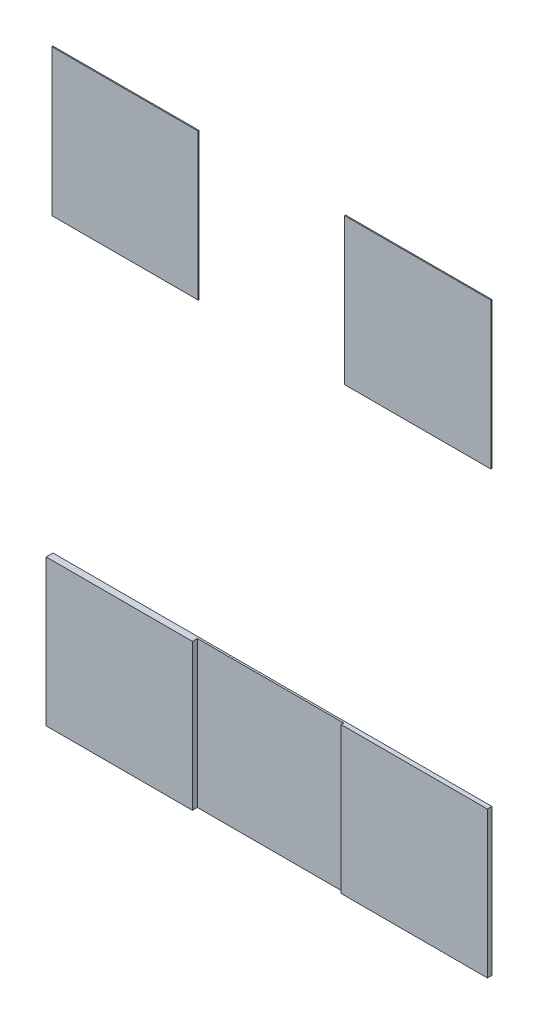
SolidWorks part; units mm, degrees
ref_plane "前视基准面" through (0, 0, 0) normal (0, 0, 1) x (1, 0, 0)
ref_plane "上视基准面" through (0, 0, 0) normal (0, 1, 0) x (1, 0, 0)
ref_plane "右视基准面" through (0, 0, 0) normal (1, 0, 0) x (0, 0, -1)
sketch "草图1" plane through (0, 0, 0) normal (0, 0, 1) x (1, 0, 0)
  line L1 (460, 460) -> (920, 460)
  line L2 (460, 460) -> (460, 920)
  line L3 (460, 920) -> (920, 920)
  line L4 (920, 460) -> (920, 920)
extrude "凸台-拉伸1" add sketch "草图1" along normal blind 21.42 flip side to cut
sketch "草图2" plane through (0, 0, 0) normal (0, 0, 1) x (1, 0, 0)
  line L1 (920, 460) -> (1380, 460)
  line L2 (920, 460) -> (920, 920)
  line L3 (920, 920) -> (1380, 920)
  line L4 (1380, 460) -> (1380, 920)
extrude "凸台-拉伸2" add sketch "草图2" along normal blind 5.8471 flip side to cut
sketch "草图3" plane through (0, 0, 0) normal (0, 0, 1) x (1, 0, 0)
  line L1 (1380, 460) -> (1840, 460)
  line L2 (1380, 460) -> (1380, 920)
  line L3 (1380, 920) -> (1840, 920)
  line L4 (1840, 460) -> (1840, 920)
extrude "凸台-拉伸3" add sketch "草图3" along normal blind 14.1569 flip side to cut
sketch "草图4" plane through (0, 0, 0) normal (0, 0, 1) x (1, 0, 0)
  line L1 (1840, 460) -> (2300, 460)
  line L2 (1840, 460) -> (1840, 920)
  line L3 (1840, 920) -> (2300, 920)
  line L4 (2300, 460) -> (2300, 920)
sketch "草图5" plane through (0, 0, 0) normal (0, 0, 1) x (1, 0, 0)
  line L1 (460, 920) -> (920, 920)
  line L2 (460, 920) -> (460, 1380)
  line L3 (460, 1380) -> (920, 1380)
  line L4 (920, 920) -> (920, 1380)
sketch "草图6" plane through (0, 0, 0) normal (0, 0, 1) x (1, 0, 0)
  line L1 (920, 920) -> (1380, 920)
  line L2 (920, 920) -> (920, 1380)
  line L3 (920, 1380) -> (1380, 1380)
  line L4 (1380, 920) -> (1380, 1380)
sketch "草图7" plane through (0, 0, 0) normal (0, 0, 1) x (1, 0, 0)
  line L1 (1380, 920) -> (1840, 920)
  line L2 (1380, 920) -> (1380, 1380)
  line L3 (1380, 1380) -> (1840, 1380)
  line L4 (1840, 920) -> (1840, 1380)
sketch "草图8" plane through (0, 0, 0) normal (0, 0, 1) x (1, 0, 0)
  line L1 (1840, 920) -> (2300, 920)
  line L2 (1840, 920) -> (1840, 1380)
  line L3 (1840, 1380) -> (2300, 1380)
  line L4 (2300, 920) -> (2300, 1380)
sketch "草图9" plane through (0, 0, 0) normal (0, 0, 1) x (1, 0, 0)
  line L1 (460, 1380) -> (920, 1380)
  line L2 (460, 1380) -> (460, 1840)
  line L3 (460, 1840) -> (920, 1840)
  line L4 (920, 1380) -> (920, 1840)
sketch "草图10" plane through (0, 0, 0) normal (0, 0, 1) x (1, 0, 0)
  line L1 (920, 1380) -> (1380, 1380)
  line L2 (920, 1380) -> (920, 1840)
  line L3 (920, 1840) -> (1380, 1840)
  line L4 (1380, 1380) -> (1380, 1840)
sketch "草图11" plane through (0, 0, 0) normal (0, 0, 1) x (1, 0, 0)
  line L1 (1380, 1380) -> (1840, 1380)
  line L2 (1380, 1380) -> (1380, 1840)
  line L3 (1380, 1840) -> (1840, 1840)
  line L4 (1840, 1380) -> (1840, 1840)
sketch "草图12" plane through (0, 0, 0) normal (0, 0, 1) x (1, 0, 0)
  line L1 (1840, 1380) -> (2300, 1380)
  line L2 (1840, 1380) -> (1840, 1840)
  line L3 (1840, 1840) -> (2300, 1840)
  line L4 (2300, 1380) -> (2300, 1840)
sketch "草图13" plane through (0, 0, 0) normal (0, 0, 1) x (1, 0, 0)
  line L1 (460, 1840) -> (920, 1840)
  line L2 (460, 1840) -> (460, 2300)
  line L3 (460, 2300) -> (920, 2300)
  line L4 (920, 1840) -> (920, 2300)
extrude "凸台-拉伸4" add sketch "草图13" along normal blind 3.4008 flip side to cut
sketch "草图14" plane through (0, 0, 0) normal (0, 0, 1) x (1, 0, 0)
  line L1 (920, 1840) -> (1380, 1840)
  line L2 (920, 1840) -> (920, 2300)
  line L3 (920, 2300) -> (1380, 2300)
  line L4 (1380, 1840) -> (1380, 2300)
sketch "草图15" plane through (0, 0, 0) normal (0, 0, 1) x (1, 0, 0)
  line L1 (1380, 1840) -> (1840, 1840)
  line L2 (1380, 1840) -> (1380, 2300)
  line L3 (1380, 2300) -> (1840, 2300)
  line L4 (1840, 1840) -> (1840, 2300)
extrude "凸台-拉伸5" add sketch "草图15" along normal blind 3.4008 flip side to cut
sketch "草图16" plane through (0, 0, 0) normal (0, 0, 1) x (1, 0, 0)
  line L1 (1840, 1840) -> (2300, 1840)
  line L2 (1840, 1840) -> (1840, 2300)
  line L3 (1840, 2300) -> (2300, 2300)
  line L4 (2300, 1840) -> (2300, 2300)
sketch "草图17" plane through (0, 0, 0) normal (0, 0, 1) x (1, 0, 0)
  line L1 (460, 460) -> (920, 460)
  line L2 (460, 460) -> (460, 920)
  line L3 (460, 920) -> (920, 920)
  line L4 (920, 460) -> (920, 920)
sketch "草图18" plane through (0, 0, 0) normal (0, 0, 1) x (1, 0, 0)
  line L1 (920, 460) -> (1380, 460)
  line L2 (920, 460) -> (920, 920)
  line L3 (920, 920) -> (1380, 920)
  line L4 (1380, 460) -> (1380, 920)
sketch "草图19" plane through (0, 0, 0) normal (0, 0, 1) x (1, 0, 0)
  line L1 (1380, 460) -> (1840, 460)
  line L2 (1380, 460) -> (1380, 920)
  line L3 (1380, 920) -> (1840, 920)
  line L4 (1840, 460) -> (1840, 920)
sketch "草图20" plane through (0, 0, 0) normal (0, 0, 1) x (1, 0, 0)
  line L1 (1840, 460) -> (2300, 460)
  line L2 (1840, 460) -> (1840, 920)
  line L3 (1840, 920) -> (2300, 920)
  line L4 (2300, 460) -> (2300, 920)
sketch "草图21" plane through (0, 0, 0) normal (0, 0, 1) x (1, 0, 0)
  line L1 (460, 920) -> (920, 920)
  line L2 (460, 920) -> (460, 1380)
  line L3 (460, 1380) -> (920, 1380)
  line L4 (920, 920) -> (920, 1380)
sketch "草图22" plane through (0, 0, 0) normal (0, 0, 1) x (1, 0, 0)
  line L1 (920, 920) -> (1380, 920)
  line L2 (920, 920) -> (920, 1380)
  line L3 (920, 1380) -> (1380, 1380)
  line L4 (1380, 920) -> (1380, 1380)
sketch "草图23" plane through (0, 0, 0) normal (0, 0, 1) x (1, 0, 0)
  line L1 (1380, 920) -> (1840, 920)
  line L2 (1380, 920) -> (1380, 1380)
  line L3 (1380, 1380) -> (1840, 1380)
  line L4 (1840, 920) -> (1840, 1380)
sketch "草图24" plane through (0, 0, 0) normal (0, 0, 1) x (1, 0, 0)
  line L1 (1840, 920) -> (2300, 920)
  line L2 (1840, 920) -> (1840, 1380)
  line L3 (1840, 1380) -> (2300, 1380)
  line L4 (2300, 920) -> (2300, 1380)
sketch "草图25" plane through (0, 0, 0) normal (0, 0, 1) x (1, 0, 0)
  line L1 (460, 1380) -> (920, 1380)
  line L2 (460, 1380) -> (460, 1840)
  line L3 (460, 1840) -> (920, 1840)
  line L4 (920, 1380) -> (920, 1840)
sketch "草图26" plane through (0, 0, 0) normal (0, 0, 1) x (1, 0, 0)
  line L1 (920, 1380) -> (1380, 1380)
  line L2 (920, 1380) -> (920, 1840)
  line L3 (920, 1840) -> (1380, 1840)
  line L4 (1380, 1380) -> (1380, 1840)
sketch "草图27" plane through (0, 0, 0) normal (0, 0, 1) x (1, 0, 0)
  line L1 (1380, 1380) -> (1840, 1380)
  line L2 (1380, 1380) -> (1380, 1840)
  line L3 (1380, 1840) -> (1840, 1840)
  line L4 (1840, 1380) -> (1840, 1840)
sketch "草图28" plane through (0, 0, 0) normal (0, 0, 1) x (1, 0, 0)
  line L1 (1840, 1380) -> (2300, 1380)
  line L2 (1840, 1380) -> (1840, 1840)
  line L3 (1840, 1840) -> (2300, 1840)
  line L4 (2300, 1380) -> (2300, 1840)
sketch "草图29" plane through (0, 0, 0) normal (0, 0, 1) x (1, 0, 0)
  line L1 (460, 1840) -> (920, 1840)
  line L2 (460, 1840) -> (460, 2300)
  line L3 (460, 2300) -> (920, 2300)
  line L4 (920, 1840) -> (920, 2300)
sketch "草图30" plane through (0, 0, 0) normal (0, 0, 1) x (1, 0, 0)
  line L1 (920, 1840) -> (1380, 1840)
  line L2 (920, 1840) -> (920, 2300)
  line L3 (920, 2300) -> (1380, 2300)
  line L4 (1380, 1840) -> (1380, 2300)
sketch "草图31" plane through (0, 0, 0) normal (0, 0, 1) x (1, 0, 0)
  line L1 (1380, 1840) -> (1840, 1840)
  line L2 (1380, 1840) -> (1380, 2300)
  line L3 (1380, 2300) -> (1840, 2300)
  line L4 (1840, 1840) -> (1840, 2300)
sketch "草图32" plane through (0, 0, 0) normal (0, 0, 1) x (1, 0, 0)
  line L1 (1840, 1840) -> (2300, 1840)
  line L2 (1840, 1840) -> (1840, 2300)
  line L3 (1840, 2300) -> (2300, 2300)
  line L4 (2300, 1840) -> (2300, 2300)
